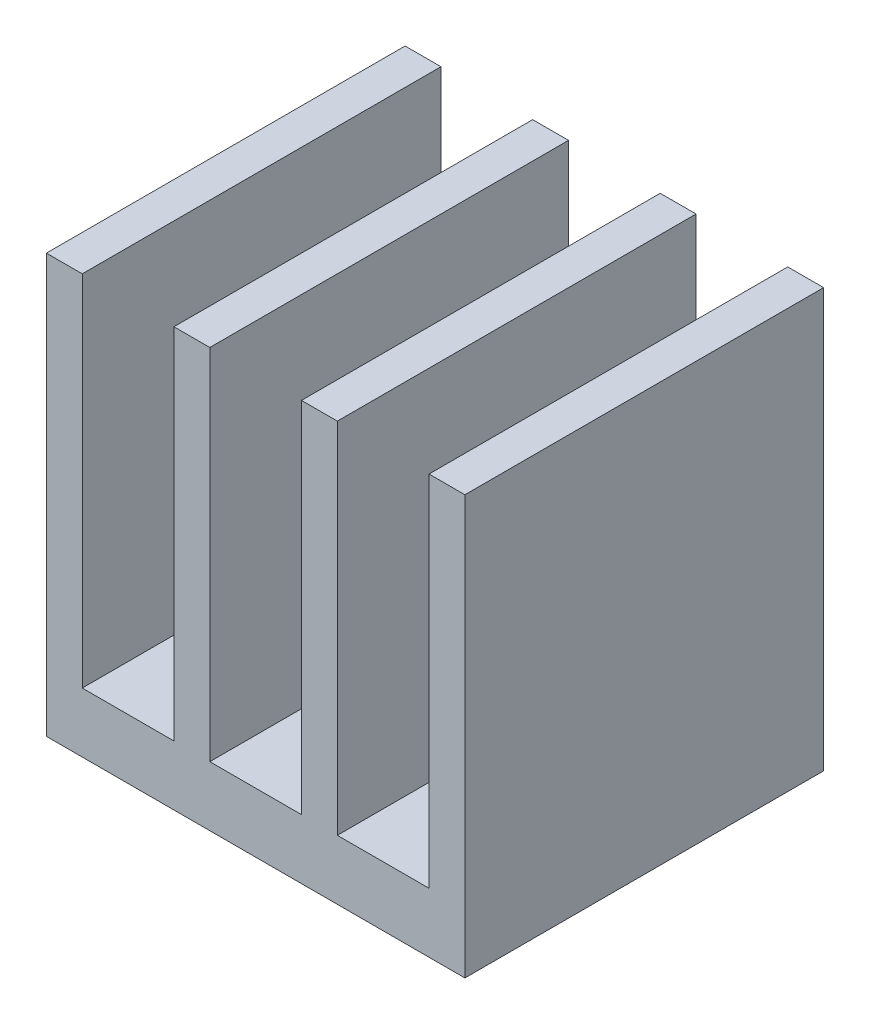
SolidWorks part; units mm, degrees
material "6061-T6 (SS)"
ref_plane "Front Plane" through (0, 0, 0) normal (0, 0, 1) x (1, 0, 0)
ref_plane "Top Plane" through (0, 0, 0) normal (0, 1, 0) x (1, 0, 0)
ref_plane "Right Plane" through (0, 0, 0) normal (1, 0, 0) x (0, 0, -1)
sketch "Sketch1" plane through (0, 0, 0) normal (0, 0, 1) x (1, 0, 0)
  line L0 (-3.5, 0) -> (3.5, 0)
  line L1 (-3.5, 0) -> (-3.5, 7)
  line L2 (-3.5, 7) -> (-2.9, 7)
  line L3 (-2.9, 7) -> (-2.9, 1)
  line L4 (-2.9, 1) -> (-1.3667, 1)
  line L5 (-1.3667, 1) -> (-1.3667, 7)
  line L6 (-1.3667, 7) -> (-0.7667, 7)
  line L7 (-0.7667, 7) -> (-0.7667, 1)
  line L8 (-0.7667, 1) -> (0.7667, 1)
  line L9 (0.7667, 1) -> (0.7667, 7)
  line L10 (0.7667, 7) -> (1.3667, 7)
  line L11 (1.3667, 7) -> (1.3667, 1)
  line L12 (1.3667, 1) -> (2.9, 1)
  line L13 (2.9, 1) -> (2.9, 7)
  line L14 (2.9, 7) -> (3.5, 7)
  line L15 (3.5, 7) -> (3.5, 0)
  dimension "D1" = 7
  dimension "D2" = 0.6
  dimension "D3" = 1
  dimension "D4" = 7
extrude "Boss-Extrude1" add sketch "Sketch1" along normal blind 6
